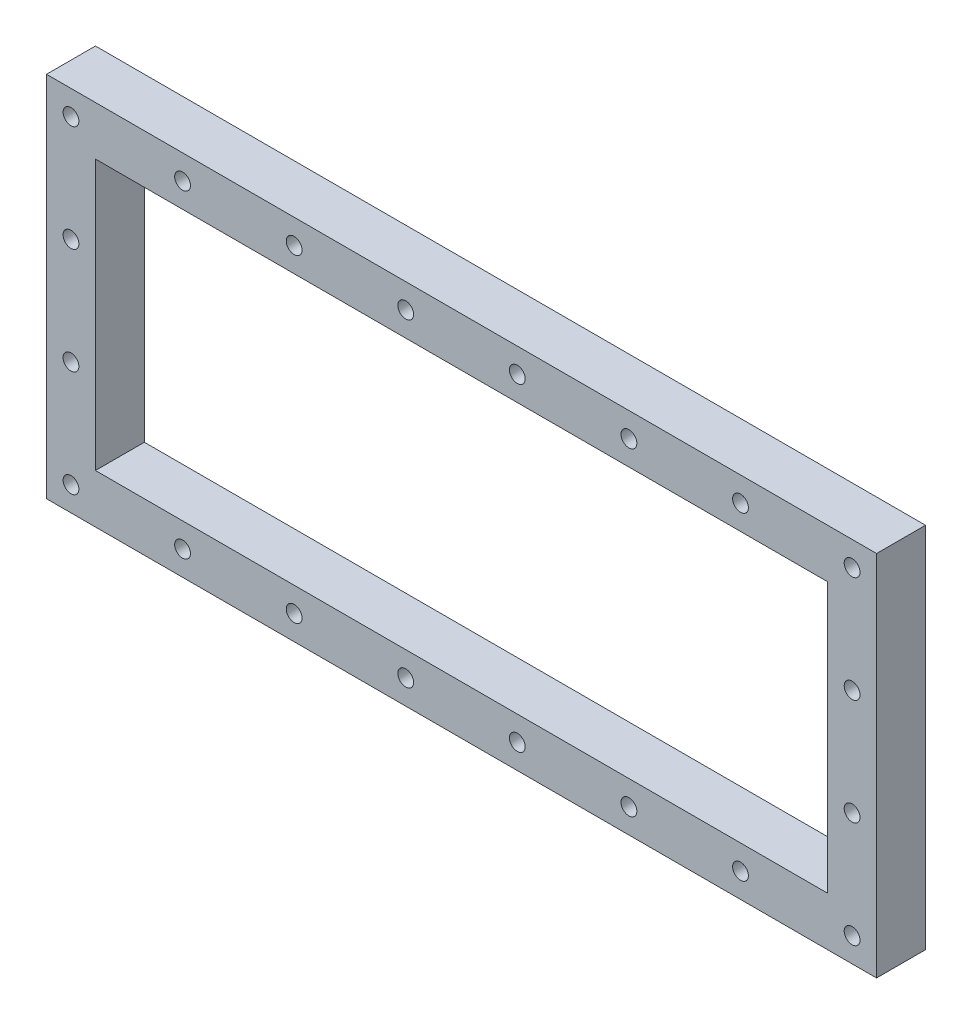
SolidWorks part; units mm, degrees
material "Acrylic (Medium-high impact)"
ref_plane "Front Plane" through (0, 0, 0) normal (0, 0, 1) x (1, 0, 0)
ref_plane "Top Plane" through (0, 0, 0) normal (0, 1, 0) x (1, 0, 0)
ref_plane "Right Plane" through (0, 0, 0) normal (1, 0, 0) x (0, 0, -1)
sketch "Sketch1" plane through (0, 0, 0) normal (0, 0, 1) x (1, 0, 0)
  line L1 (-53.85, -23.85) -> (53.85, -23.85)
  line L2 (-53.85, -23.85) -> (-53.85, 23.85)
  line L3 (-53.85, 23.85) -> (53.85, 23.85)
  line L4 (53.85, -23.85) -> (53.85, 23.85)
  line L5 (-53.85, -23.85) -> (53.85, 23.85) construction
  line L6 (-53.85, 23.85) -> (53.85, -23.85) construction
  line L7 (-50.675, 20.675) -> (50.675, 20.675) construction
  line L8 (-50.675, 20.675) -> (-50.675, -20.675) construction
  line L9 (-50.675, -20.675) -> (50.675, -20.675) construction
  line L10 (50.675, 20.675) -> (50.675, -20.675) construction
  line L11 (-47.5, 17.5) -> (47.5, 17.5)
  line L12 (-47.5, 17.5) -> (-47.5, -17.5)
  line L13 (-47.5, -17.5) -> (47.5, -17.5)
  line L14 (47.5, 17.5) -> (47.5, -17.5)
  circle A0 centre (-50.675, 20.675) radius 1.025
  circle A1 centre (50.675, 20.675) radius 1.025
  circle A2 centre (-50.675, -20.675) radius 1.025
  circle A3 centre (50.675, -20.675) radius 1.025
  circle A4 centre (-7.2393, 20.675) radius 1.025
  circle A5 centre (-7.2393, -20.675) radius 1.025
  circle A8 centre (-36.1964, 20.675) radius 1.025
  circle A9 centre (-21.7179, 20.675) radius 1.025
  circle A10 centre (7.2393, 20.675) radius 1.025
  circle A11 centre (21.7179, 20.675) radius 1.025
  circle A12 centre (-50.675, 6.8917) radius 1.025
  circle A13 centre (-50.675, -6.8917) radius 1.025
  circle A14 centre (50.675, 6.8917) radius 1.025
  circle A15 centre (50.675, -6.8917) radius 1.025
  circle A16 centre (7.2393, -20.675) radius 1.025
  circle A17 centre (21.7179, -20.675) radius 1.025
  circle A18 centre (-21.7179, -20.675) radius 1.025
  circle A19 centre (-36.1964, -20.675) radius 1.025
  circle A20 centre (36.1964, 20.675) radius 1.025
  circle A21 centre (36.1964, -20.675) radius 1.025
  point P0 (0, 0)
  dimension "D7" = 2.05
  dimension "D1" = 107.7
  dimension "D2" = 47.7
  dimension "D3" = 3.175
  dimension "D4" = 3.175
  dimension "D5" = 3.175
  dimension "D6" = 3.175
  dimension "D8" = 41.35
  dimension "D9" = 13.7833
  dimension "D10" = 13.7833
  dimension "D11" = 101.35
  dimension "D12" = 14.4786
  dimension "D13" = 14.4786
  dimension "D14" = 14.4786
  dimension "D15" = 14.4786
  dimension "D16" = 6.35
  dimension "D17" = 6.35
  dimension "D18" = 6.35
  dimension "D19" = 6.35
  dimension "D20" = 14.4786
  dimension "D21" = 14.4786
extrude "Boss-Extrude1" add sketch "Sketch1" along normal blind 6.35 contours L1 L4 L3 L2 A19 A18 A17 A16 A15 A14 A13 A12 A11 A10 A9 A8 A5 A4 A3 A2 A1 A0 | L12 L11 L14 L13
